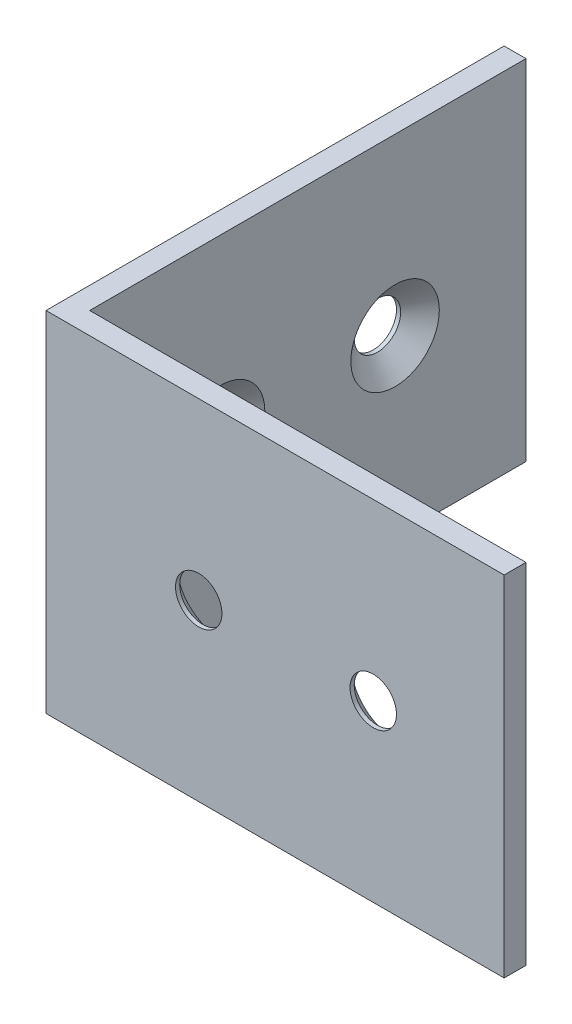
SolidWorks part; units mm, degrees
ref_plane "Front Plane" through (0, 0, 0) normal (0, 0, 1) x (1, 0, 0)
ref_plane "Top Plane" through (0, 0, 0) normal (0, 1, 0) x (1, 0, 0)
ref_plane "Right Plane" through (0, 0, 0) normal (1, 0, 0) x (0, 0, -1)
sketch "Sketch1" plane through (0, 0, 0) normal (0, 1, 0) x (1, 0, 0)
  line L0 (0, 0) -> (0, 63.5)
  line L1 (0, 63.5) -> (3.175, 63.5)
  line L2 (3.175, 63.5) -> (3.175, 0)
  line L3 (3.175, 0) -> (66.675, 0)
  line L4 (66.675, 0) -> (66.675, -3.175)
  line L5 (66.675, -3.175) -> (0, -3.175)
  line L6 (0, -3.175) -> (0, 0)
  dimension "D1" = 63.5
  dimension "D2" = 63.5
  dimension "D3" = 3.175
  dimension "D4" = 3.175
extrude "Boss-Extrude1" add sketch "Sketch1" along normal blind 50.8
hole_wizard "CSK for 1/4 Flat Head Machine Screw (100)1" positions "Sketch3" profile "Sketch4" countersink size "1/4" standard "ANSI Inch" end condition through all
sketch "Sketch3" plane through (3.175, 0, 0) normal (1, 0, 0) x (0, 0, -1)
  line L0 (63.5, 25.4) -> (3.7819, 25.4) construction
  line L1 (63.5, 50.8) -> (63.5, 0) construction
  point P0 (19.05, 25.4)
  point P2 (44.45, 25.4)
  point P11 (16.9088, 25.4)
  point P12 (49.2504, 25.4)
  dimension "D1" = 19.05
  dimension "D2" = 25.4
sketch "Sketch4" plane through (3.175, 25.4, -19.05) normal (0, 1, 0) x (0, 0, -1)
  line L0 (0, 0) -> (0, 3.175)
  line L1 (0, 3.175) -> (3.3782, 3.175)
  line L2 (3.3782, 3.175) -> (3.3782, 2.5682)
  line L3 (3.3782, 2.5682) -> (6.4389, 0)
  line L5 (6.4389, 0) -> (0, 0)
  line L6 (-3.3782, 2.5682) -> (-6.4389, 0) construction
  line L11 (0, -6.35) -> (0, 107.95) construction
  dimension "Thru Hole Dia." = 6.7564
  dimension "Thru Hole Depth" = 3.175
  dimension "Near C'Sink Dia." = 12.8778
  dimension "Near C'Sink Angle" = 100
hole_wizard "CSK for 1/4 Flat Head Machine Screw (100)2" positions "Sketch5" profile "Sketch6" countersink size "1/4" standard "ANSI Inch" end condition through all
sketch "Sketch5" plane through (0, 0, 0) normal (0, 0, -1) x (-1, 0, 0)
  line L0 (-66.675, 50.8) -> (-66.675, 0) construction
  point P0 (-47.625, 25.4)
  point P2 (-22.225, 25.4)
  dimension "D1" = 19.05
  dimension "D2" = 25.4
sketch "Sketch6" plane through (47.625, 25.4, 0) normal (1, 0, 0) x (0, 1, 0)
  line L0 (0, 0) -> (0, 3.175)
  line L1 (0, 3.175) -> (3.3782, 3.175)
  line L2 (3.3782, 3.175) -> (3.3782, 2.5682)
  line L3 (3.3782, 2.5682) -> (6.4389, 0)
  line L5 (6.4389, 0) -> (0, 0)
  line L6 (-3.3782, 2.5682) -> (-6.4389, 0) construction
  line L11 (0, -6.35) -> (0, 107.95) construction
  dimension "Thru Hole Dia." = 6.7564
  dimension "Thru Hole Depth" = 3.175
  dimension "Near C'Sink Dia." = 12.8778
  dimension "Near C'Sink Angle" = 100
